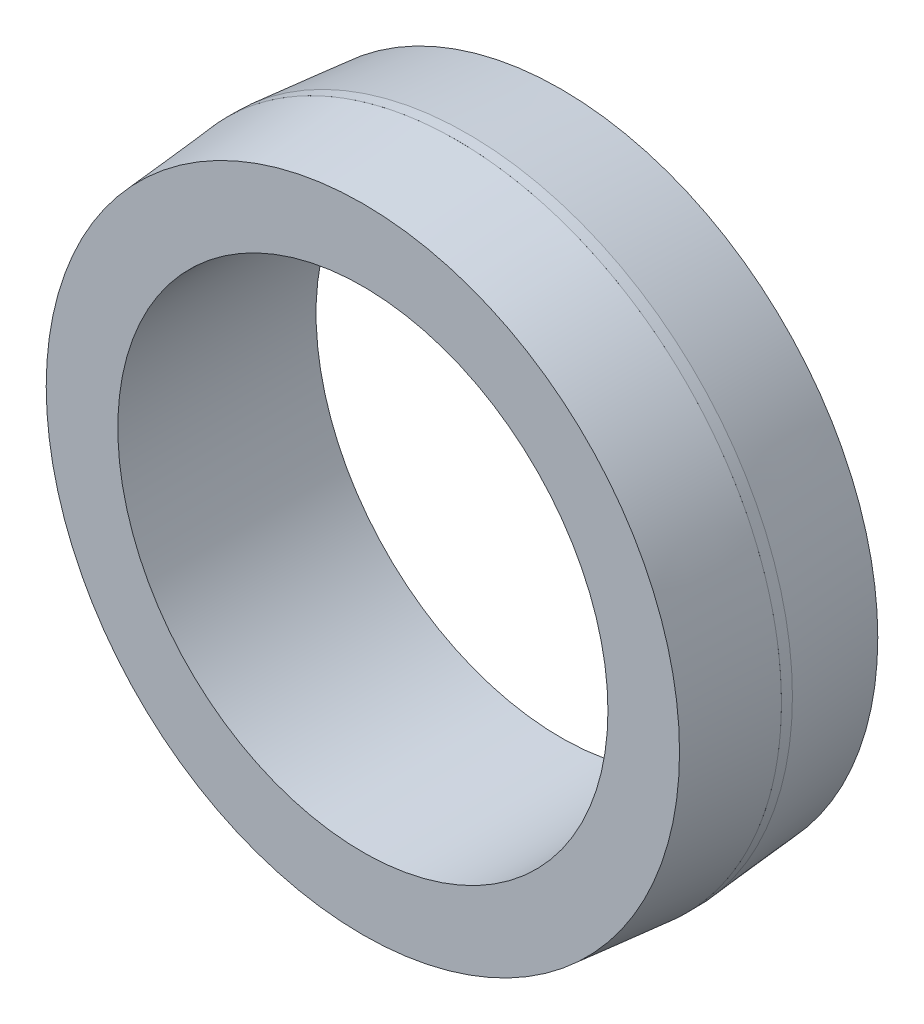
SolidWorks part; units mm, degrees
ref_plane "Front Plane" through (0, 0, 0) normal (0, 0, 1) x (1, 0, 0)
ref_plane "Top Plane" through (0, 0, 0) normal (0, 1, 0) x (1, 0, 0)
ref_plane "Right Plane" through (0, 0, 0) normal (1, 0, 0) x (0, 0, -1)
sketch "Sketch10" plane through (0, 0, 0) normal (0, 1, 0) x (1, 0, 0)
  line L0 (0, 66.8695) -> (0, -59.5921) construction
  line L4 (57.5, 17) -> (57.5, 0)
  line L5 (59, 0) -> (57.5, 17)
  line L6 (57.5, 0) -> (59, 0) construction
  line L7 (57.5, 0) -> (59, 0)
  dimension "D4" = 57.5
  dimension "D5" = 17
revolve "Revolve1" add sketch "Sketch10" angle 360 about L0
sketch "Sketch11" plane through (0, 0, 0) normal (0, 0, 1) x (1, 0, 0)
  circle A0 centre (0, 0) radius 44.5
  circle A1 centre (0, 0) radius 57.5
  dimension "D1" = 89
  dimension "D2" = 115
extrude "Boss-Extrude3" add sketch "Sketch11" against normal blind 17
sketch "Sketch12" plane through (0, 0, 0) normal (0, 0, 1) x (1, 0, 0)
  circle A0 centre (0, 0) radius 44.5
  circle A1 centre (0, 0) radius 59
extrude "Boss-Extrude4" add sketch "Sketch12" along normal blind 1
mirror "Mirror11" about plane through (0, 0, 1) normal (0, 0, 1) of "Boss-Extrude4", "Revolve1"
ref_plane "Plane4" through (0, 0, 0) normal (0, 1, 0) x (1, 0, 0)
sketch "Sketch14" plane through (0, 0, 0) normal (0, 1, 0) x (1, 0, 0)
  line L0 (0, 34.2081) -> (0, -10.3772) construction
  line L2 (-57.5, -2) -> (-57.5, -19)
  line L4 (-59, -1.969) -> (-57.5, -2)
  line L6 (-57.5, -19) -> (-59, -1.969)
  line L8 (-59, -2) -> (59, -2) construction
revolve "Revolve2" add sketch "Sketch14" angle 360 about L0
sketch "Sketch15" plane through (0, 0, 2) normal (0, 0, 1) x (1, 0, 0)
  circle A0 centre (0, 0) radius 44.5
  circle A1 centre (0, 0) radius 57.5
extrude "Boss-Extrude5" add sketch "Sketch15" along normal blind 17
